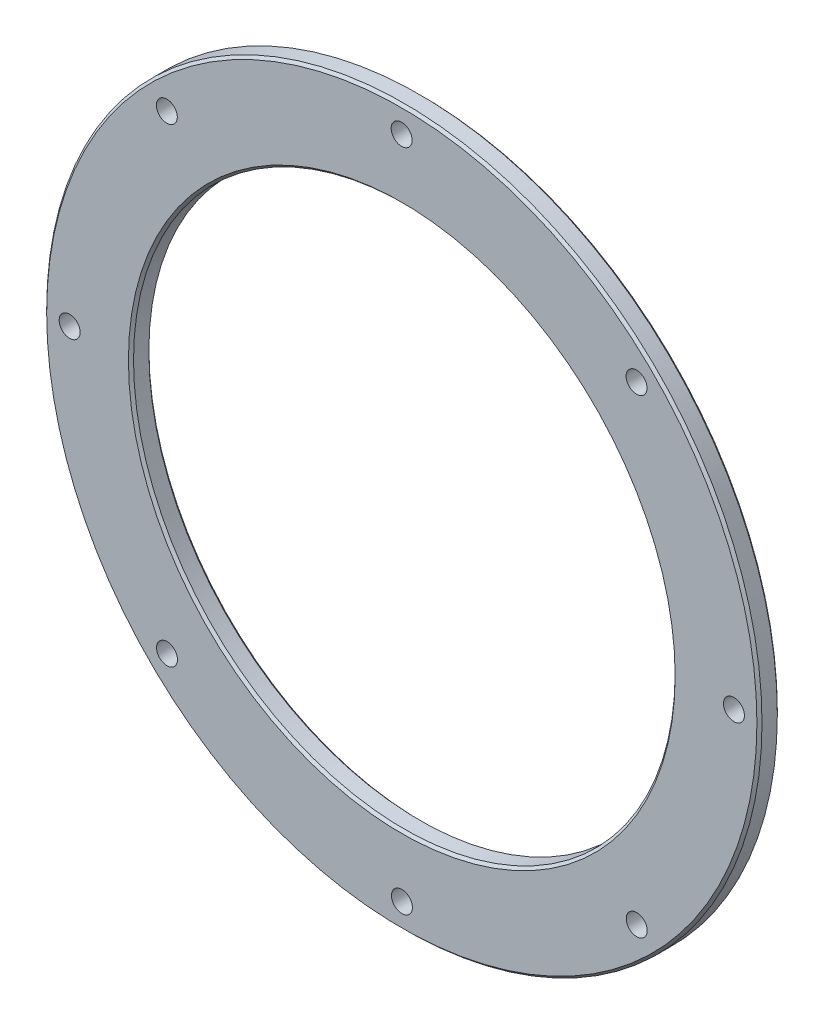
SolidWorks part; units mm, degrees
ref_plane "Front Plane" through (0, 0, 0) normal (0, 0, 1) x (1, 0, 0)
ref_plane "Top Plane" through (0, 0, 0) normal (0, 1, 0) x (1, 0, 0)
ref_plane "Right Plane" through (0, 0, 0) normal (1, 0, 0) x (0, 0, -1)
ref_plane "Plane1" through (0, 0, -8) normal (0, 0, -1) x (-1, 0, 0)
sketch "Sketch1" plane through (0, 0, -8) normal (0, 0, -1) x (-1, 0, 0)
  circle A0 centre (91.9603, 91.8875) radius 4.1
  circle A1 centre (130, -0.0514) radius 4.1
  circle A2 centre (91.8875, -91.9603) radius 4.1
  circle A3 centre (-0.0514, -130) radius 4.1
  circle A4 centre (-91.9603, -91.8875) radius 4.1
  circle A5 centre (-130, 0.0514) radius 4.1
  circle A6 centre (-91.8875, 91.9603) radius 4.1
  circle A7 centre (0.0514, 130) radius 4.1
  circle A8 centre (0, 0) radius 106
  circle A9 centre (0, 0) radius 140
  dimension "D1" = 212
  dimension "D2" = 280
extrude "Boss-Extrude1" add sketch "Sketch1" against normal blind 8
chamfer "Chamfer2" distance 1 angle 45 4 edges at (106, 0, 0) (106, 0, -8) (140, 0, -8) (140, 0, 0)
